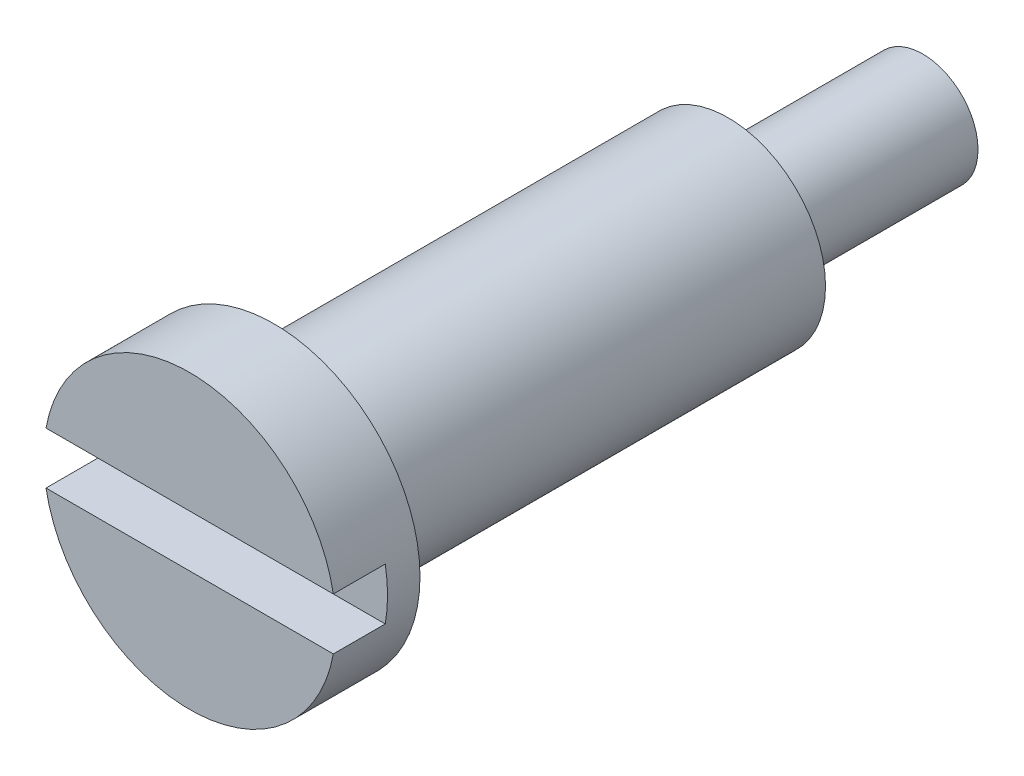
SolidWorks part; units mm, degrees
material "Stainless Steel (ferritic)"
ref_plane "Front" through (0, 0, 0) normal (0, 0, 1) x (1, 0, 0)
ref_plane "Top" through (0, 0, 0) normal (0, 1, 0) x (1, 0, 0)
ref_plane "Right" through (0, 0, 0) normal (1, 0, 0) x (0, 0, -1)
sketch "Sketch2" plane through (0, 0, 0) normal (0, 0, 1) x (1, 0, 0)
  circle A0 centre (0, 0) radius 2.25
extrude "Boss-Extrude1" add sketch "Sketch2" along normal blind 1.3
sketch "Sketch3" plane through (0, 0, 1.3) normal (0, 0, 1) x (1, 0, 0)
  line L1 (-2.445, 0.4) -> (2.445, 0.4)
  line L2 (-2.445, 0.4) -> (-2.445, -0.4)
  line L3 (-2.445, -0.4) -> (2.445, -0.4)
  line L4 (2.445, 0.4) -> (2.445, -0.4)
  line L5 (-2.445, 0.4) -> (2.445, -0.4) construction
  line L6 (-2.445, -0.4) -> (2.445, 0.4) construction
  point P0 (0, 0)
  dimension "D1" = 0.8
extrude "Cut-Extrude1" cut sketch "Sketch3" against normal blind 0.8
sketch "Sketch4" plane through (0, 0, 0) normal (0, 0, -1) x (-1, 0, 0)
  circle A0 centre (0, 0) radius 1.5
extrude "Boss-Extrude2" add sketch "Sketch4" along normal blind 7
cosmetic thread "Cosmetic Thread2" parameters "D1"=6, "D2"=2.439
sketch "Sketch5" plane through (0, 0, -7) normal (0, 0, -1) x (-1, 0, 0)
  circle A0 centre (0, 0) radius 0.85
extrude "Boss-Extrude3" add sketch "Sketch5" along normal blind 3
